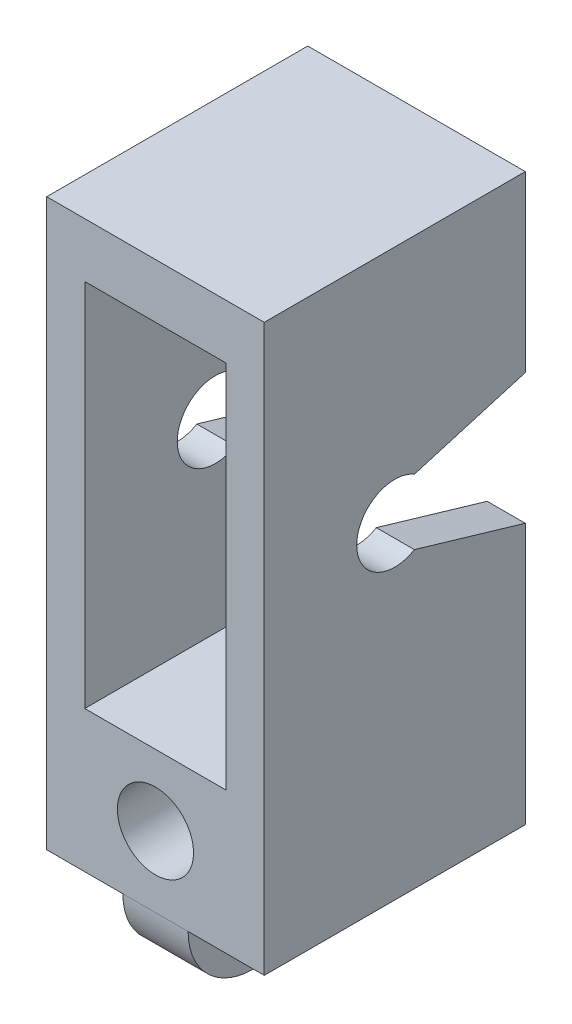
SolidWorks part; units mm, degrees
ref_plane "Front Plane" through (0, 0, 0) normal (0, 0, 1) x (1, 0, 0)
ref_plane "Top Plane" through (0, 0, 0) normal (0, 1, 0) x (1, 0, 0)
ref_plane "Right Plane" through (0, 0, 0) normal (1, 0, 0) x (0, 0, -1)
sketch "Sketch1" plane through (0, 0, 0) normal (1, 0, 0) x (0, 0, -1)
  line L0 (0, 0) -> (0, 67.2198) construction
  line L1 (-6, 0) -> (6, 0)
  line L2 (6, 0) -> (6, 12)
  line L3 (0.9014, 16.5) -> (6, 18)
  line L4 (0, 15) -> (6.3089, 15) construction
  line L5 (0.9014, 13.5) -> (6, 12)
  line L6 (6, 26) -> (-6, 26)
  line L7 (-6, 0) -> (-6, 26)
  line L8 (6, 18) -> (6, 26)
  arc A0 (0.9014, 16.5) -> (0.9014, 13.5) centre (0, 15) ccw
  circle A1 centre (0, 15) radius 8 construction
  point P14 (0, 26)
  dimension "D1" = 3.5
  dimension "D2" = 16
  dimension "D3" = 26
  dimension "D4" = 15
  dimension "D5" = 12
  dimension "D6" = 3
  dimension "D7" = 6
extrude "Boss-Extrude1" add sketch "Sketch1" along normal mid plane 10
sketch "Sketch2" plane through (0, 0, 6) normal (0, 0, 1) x (1, 0, 0)
  line L0 (5, 26) -> (-5, 26) construction
  line L1 (-3.25, 23.5) -> (3.25, 23.5)
  line L2 (-3.25, 23.5) -> (-3.25, 6.5)
  line L3 (-3.25, 6.5) -> (3.25, 6.5)
  line L4 (0, 23.5) -> (0, 6.5) construction
  line L5 (5, 0) -> (-5, 0) construction
  line L6 (3.25, 23.5) -> (3.25, 6.5)
  dimension "D1" = 2.5
  dimension "D2" = 6.5
  dimension "D3" = 6.5
extrude "Cut-Extrude1" cut sketch "Sketch2" against normal blind 20
sketch "Sketch3" plane through (0, 0, 0) normal (0, 0, 1) x (1, 0, 0)
  line L0 (0, 0) -> (0, 6.5) construction
  line L1 (2.75, 4.8377) -> (0, 6.4254) construction
  line L2 (0, 6.4254) -> (-2.75, 4.8377) construction
  line L3 (-2.75, 4.8377) -> (-2.75, 1.6623) construction
  line L4 (-2.75, 1.6623) -> (0, 0.0746) construction
  line L5 (0, 0.0746) -> (2.75, 1.6623) construction
  line L6 (2.75, 1.6623) -> (2.75, 4.8377) construction
  line L7 (-3.25, 6.5) -> (3.25, 6.5) construction
  line L8 (-2.75, 0) -> (2.75, 0)
  line L9 (-2.75, 0) -> (-2.75, 5.1841)
  line L10 (2.75, 0) -> (2.75, 5.1841)
  line L12 (5, 0) -> (-5, 0) construction
  line L13 (2.75, 5.1841) -> (0, 6.7718)
  line L14 (0, 6.7718) -> (-2.75, 5.1841)
  circle A0 centre (0, 3.25) radius 2.75 construction
  dimension "D1" = 5.5
  dimension "D2" = 0.3
  dimension "D3" = 0.3
extrude "Cut-Extrude2" cut sketch "Sketch3" against normal blind 2.5
sketch "Sketch4" plane through (0, 0, 0) normal (0, 0, 1) x (1, 0, 0)
  circle A0 centre (0, 3.25) radius 1.75
  dimension "D1" = 3.5
extrude "Cut-Extrude3" cut sketch "Sketch4" against normal mid plane 20
sketch "Sketch5" plane through (0, 0, 0) normal (1, 0, 0) x (0, 0, -1)
  line L0 (6, 1.5) -> (6, 5) construction
  line L1 (-6, 0) -> (6, 0) construction
  line L2 (6, 5) -> (6, 6.5)
  line L3 (6, 1.5) -> (6, 0)
  line L4 (0, 0) -> (-6, 0) construction
  line L5 (-4.4, 0) -> (-6, 0)
  line L6 (-1.6, 0) -> (0, 0)
  line L7 (9.25, 3.25) -> (9.25, -5.9831) construction
  line L8 (-6, 26) -> (-6, 0) construction
  arc A0 (6, 5) -> (6, 1.5) centre (6, 3.25) cw
  arc A1 (6, 6.5) -> (6, 0) centre (6, 3.25) cw
  arc A2 (-6, 0) -> (0, 0) centre (-3, 0) ccw
  arc A3 (-4.4, 0) -> (-1.6, 0) centre (-3, 0) ccw
  dimension "D1" = 1.4
  dimension "D2" = 15.25
extrude "Boss-Extrude2" add sketch "Sketch5" along normal mid plane 3
